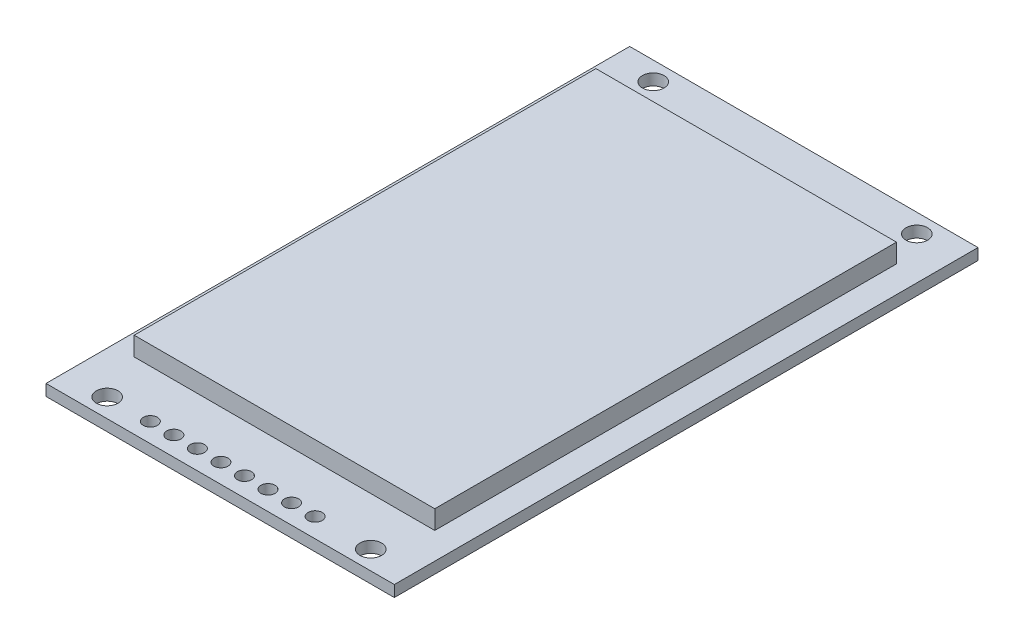
SolidWorks part; units mm, degrees
ref_plane "Front Plane" through (0, 0, 0) normal (0, 0, 1) x (1, 0, 0)
ref_plane "Top Plane" through (0, 0, 0) normal (0, 1, 0) x (1, 0, 0)
ref_plane "Right Plane" through (0, 0, 0) normal (1, 0, 0) x (0, 0, -1)
sketch "Sketch1" plane through (0, 0, 0) normal (0, 1, 0) x (1, 0, 0)
  line L0 (32.5, 60) -> (32.5, 2) construction
  line L1 (0, 0) -> (37, 0)
  line L2 (0, 0) -> (0, 62)
  line L3 (0, 62) -> (37, 62)
  line L4 (37, 0) -> (37, 62)
  line L5 (32.5, 2) -> (4.5, 2) construction
  line L6 (4.5, 2) -> (4.5, 60) construction
  line L7 (4.5, 60) -> (32.5, 60) construction
  line L8 (18.5, 2) -> (18.5, 0) construction
  line L9 (4.5, 31) -> (0, 31) construction
  circle A0 centre (32.5, 60) radius 1.15
  circle A1 centre (4.5, 60) radius 1.15
  circle A2 centre (32.5, 2) radius 1.15
  circle A3 centre (4.5, 2) radius 1.15
  dimension "D3" = 2.3
  dimension "D1" = 37
  dimension "D2" = 62
  dimension "D4" = 28
  dimension "D5" = 58
extrude "Boss-Extrude1" add sketch "Sketch1" along normal blind 1.2
sketch "Sketch2" plane through (0, 1.2, 0) normal (0, 1, 0) x (1, 0, 0)
  line L1 (2.2462, 56.1674) -> (34.1749, 56.1674)
  line L2 (2.2462, 56.1674) -> (2.2462, 7.1205)
  line L3 (2.2462, 7.1205) -> (34.1749, 7.1205)
  line L4 (34.1749, 56.1674) -> (34.1749, 7.1205)
extrude "Boss-Extrude2" add sketch "Sketch2" along normal blind 2
sketch "Sketch3" plane through (0, 1.2, 0) normal (0, 1, 0) x (1, 0, 0)
  circle A0 centre (9.0316, 2.0507) radius 0.75
  circle A1 centre (11.5316, 2.0507) radius 0.75
  circle A2 centre (14.0316, 2.0507) radius 0.75
  circle A3 centre (16.5316, 2.0507) radius 0.75
  circle A4 centre (19.0316, 2.0507) radius 0.75
  circle A5 centre (21.5316, 2.0507) radius 0.75
  circle A6 centre (24.0316, 2.0507) radius 0.75
  circle A7 centre (26.5316, 2.0507) radius 0.75
  dimension "D1" = 1.5
  dimension "D2" = 8
extrude "Cut-Extrude1" cut sketch "Sketch3" against normal through all
